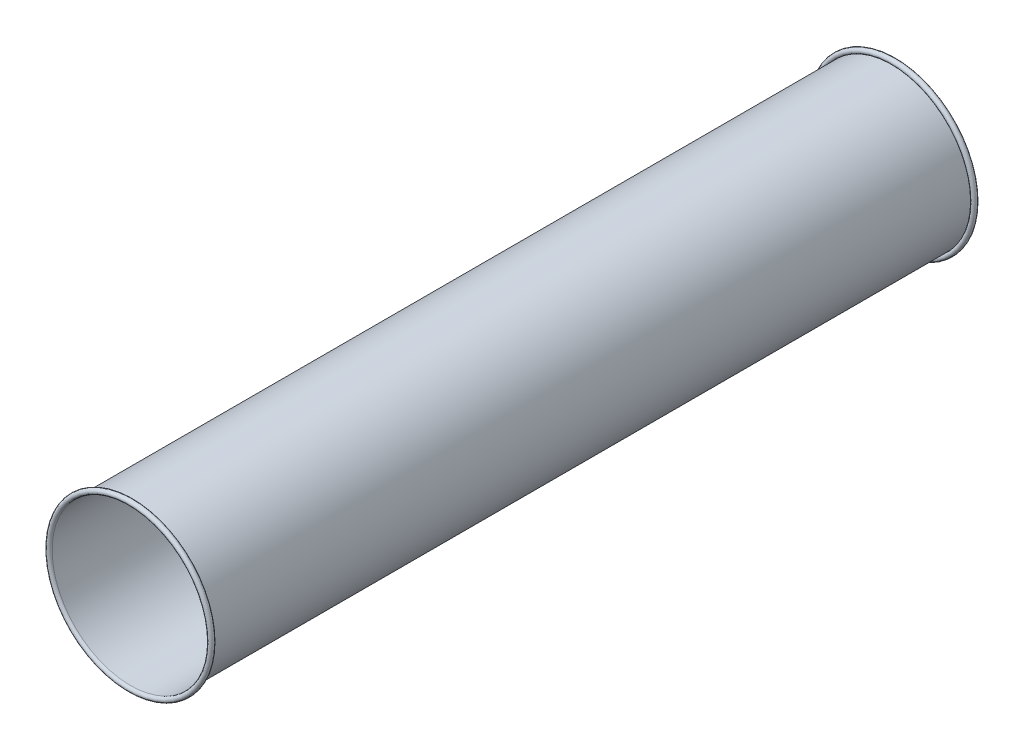
SolidWorks part; units mm, degrees
other "2538K116_1" parameters "D1"=3.3784, "Rolled Edge"=10.16, "Gauge"=0.9525, "ID (Female)"=404.876, "Overall Length"=1492.25, "OD"=76.2, "Length"=1492.25, "ID"=304.0075, "Duct Size"=304.8
ref_plane "Front" through (0, 0, 0) normal (0, 0, 1) x (1, 0, 0)
ref_plane "Top" through (0, 0, 0) normal (0, 1, 0) x (1, 0, 0)
ref_plane "Right" through (0, 0, 0) normal (1, 0, 0) x (0, 0, -1)
sketch "Sketch1" plane through (0, 0, 0) normal (1, 0, 0) x (0, 0, -1)
  line L0 (-746.125, 0) -> (746.125, 0) construction
  line L1 (-746.125, -152.0038) -> (-746.125, 152.0038) construction
  line L2 (746.125, -152.0038) -> (746.125, 152.0038) construction
  line L3 (-746.125, 152.0038) -> (-746.125, 152.9563)
  line L4 (-746.125, 152.9563) -> (746.125, 152.9563) construction
  line L5 (0, 0) -> (0, 152.9563) construction
  line L6 (-746.125, -152.0038) -> (-746.125, -152.9563) construction
  line L7 (-746.125, -152.9563) -> (746.125, -152.9563) construction
  line L8 (746.125, -152.9563) -> (746.125, -152.0038) construction
  line L9 (-746.125, 152.0038) -> (746.125, 152.0038) construction
  line L10 (-735.965, 152.9563) -> (-735.965, 157.0838) construction
  line L11 (-746.125, 152.9563) -> (-746.125, 157.0838) construction
  line L12 (0, 152.4) -> (0, -152.4) construction
  circle A0 centre (-741.045, 157.0838) radius 5.08 construction
  point P15 (0, 0)
  point P18 (-442.1175, 0)
  point P19 (-735.965, 152.9563)
  point P20 (-746.125, -152.0038)
  point P24 (-746.125, 152.0038)
  point P25 (-746.125, 157.0838)
  point P26 (-735.965, 157.0838)
  point P27 (442.1175, 0)
  dimension "Gauge" = 0.9525
  dimension "Rolled Edge" = 10.16
  dimension "D1" = 304.0075
sketch "Sketch2" plane through (0, 0, 0) normal (1, 0, 0) x (0, 0, -1)
  line L0 (0, 152.9563) -> (-741.045, 152.9563)
  line L1 (-746.125, 152.0038) -> (746.125, 152.0038) construction
  line L2 (-746.125, 152.9563) -> (746.125, 152.9563) construction
  line L3 (-741.045, 152.0038) -> (0, 152.0038)
  line L4 (-737.7583, 153.2103) -> (-739.6194, 153.2103)
  line L5 (0, 152.9563) -> (0, 152.0038)
  arc A0 (-739.6194, 153.2103) -> (-741.045, 152.9563) centre (-741.045, 157.0838) ccw
  arc A1 (-741.045, 152.0038) -> (-737.7583, 153.2103) centre (-741.045, 157.0838) cw
  circle A2 centre (-741.045, 157.0838) radius 5.08 construction
  dimension "D1" = 0.254
revolve "Revolve1" add sketch "Sketch2" angle 360 about L0
mirror "Mirror1" about plane through (0, 152.9563, 0) normal (0, 0, 1) of bodies 110
equation "\"D1@Sketch1\"=\"ID@Sketch1\""
